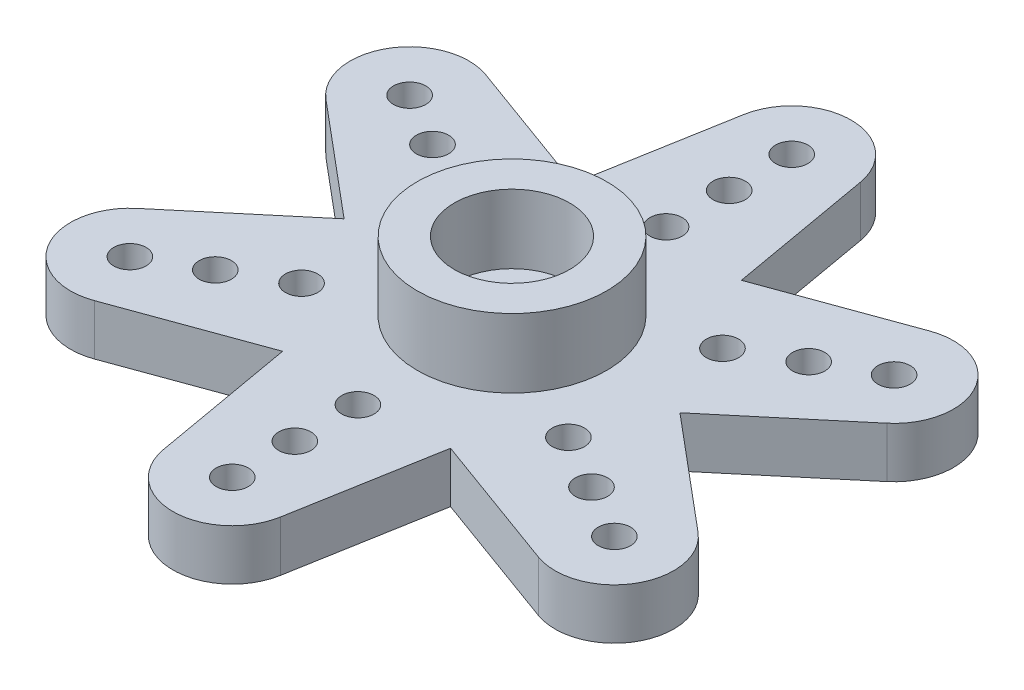
SolidWorks part; units mm, degrees
ref_plane "Front Plane" through (0, 0, 0) normal (0, 0, 1) x (1, 0, 0)
ref_plane "Top Plane" through (0, 0, 0) normal (0, 1, 0) x (1, 0, 0)
ref_plane "Right Plane" through (0, 0, 0) normal (1, 0, 0) x (0, 0, -1)
sketch "Sketch1" plane through (0, 0, 0) normal (0, 1, 0) x (1, 0, 0)
  circle A0 centre (0, 0) radius 15.75
  dimension "D1" = 31.5
extrude "Boss-Extrude1" add sketch "Sketch1" along normal blind 2.35
sketch "Sketch2" plane through (0, 2.35, 0) normal (0, 1, 0) x (1, 0, 0)
  line L0 (0, 0) -> (0, 50000) construction
  line L1 (0, 0) -> (-43301.2702, 25000) construction
  line L2 (0, 0) -> (-25000, 43301.2702) construction
  line L3 (-3.9, 6.755) -> (8678.5089, 49247.1426) construction
  line L4 (-3.9, 6.755) -> (-46988.531, 17107.7622) construction
  line L5 (-3.9, 6.755) -> (-2.7157, 13.4712)
  line L6 (0, 15.75) -> (0, 13.7424)
  line L7 (0, 12.2424) -> (0, 10.8376)
  line L8 (0, 9.3376) -> (0, 7.9061)
  line L11 (-3.9, 6.755) -> (-46988.531, 17107.7622) construction
  line L12 (0, 0) -> (-43301.2702, 25000) construction
  line L13 (-5.5478, 3.203) -> (0, 0)
  line L14 (-8.0866, 4.6688) -> (-6.8469, 3.953)
  line L15 (-10.6022, 6.1212) -> (-9.3856, 5.4188)
  line L16 (-13.6399, 7.875) -> (-11.9012, 6.8712)
  line L17 (-3.9, 6.755) -> (-10.3085, 9.0875)
  line L18 (3.9, 6.755) -> (10.3085, 9.0875)
  line L19 (3.9, 6.755) -> (2.7157, 13.4712)
  line L20 (0, 15.75) -> (0, 13.7424)
  line L21 (0, 12.2424) -> (0, 10.8376)
  line L22 (0, 9.3376) -> (0, 7.9061)
  line L23 (0, 6.4061) -> (0, 0)
  line L24 (5.5478, 3.203) -> (0, 0)
  line L25 (8.0866, 4.6688) -> (6.8469, 3.953)
  line L26 (10.6022, 6.1212) -> (9.3856, 5.4188)
  line L27 (13.6399, 7.875) -> (11.9012, 6.8712)
  line L28 (7.8, 0) -> (13.0243, -4.3837)
  line L29 (7.8, 0) -> (13.0243, 4.3837)
  line L30 (13.6399, 7.875) -> (11.9012, 6.8712)
  line L31 (10.6022, 6.1212) -> (9.3856, 5.4188)
  line L32 (8.0866, 4.6688) -> (6.8469, 3.953)
  line L33 (5.5478, 3.203) -> (0, 0)
  line L34 (5.5478, -3.203) -> (0, 0)
  line L35 (8.0866, -4.6688) -> (6.8469, -3.953)
  line L36 (10.6022, -6.1212) -> (9.3856, -5.4188)
  line L37 (13.6399, -7.875) -> (11.9012, -6.8712)
  line L38 (3.9, -6.755) -> (2.7157, -13.4712)
  line L39 (3.9, -6.755) -> (10.3085, -9.0875)
  line L40 (13.6399, -7.875) -> (11.9012, -6.8712)
  line L41 (10.6022, -6.1212) -> (9.3856, -5.4188)
  line L42 (8.0866, -4.6688) -> (6.8469, -3.953)
  line L43 (5.5478, -3.203) -> (0, 0)
  line L44 (0, -6.4061) -> (0, 0)
  line L45 (0, -9.3376) -> (0, -7.9061)
  line L46 (0, -12.2424) -> (0, -10.8376)
  line L47 (0, -15.75) -> (0, -13.7424)
  line L48 (-3.9, -6.755) -> (-10.3085, -9.0875)
  line L49 (-3.9, -6.755) -> (-2.7157, -13.4712)
  line L50 (0, -15.75) -> (0, -13.7424)
  line L51 (0, -12.2424) -> (0, -10.8376)
  line L52 (0, -9.3376) -> (0, -7.9061)
  line L53 (0, -6.4061) -> (0, 0)
  line L54 (-5.5478, -3.203) -> (0, 0)
  line L55 (-8.0866, -4.6688) -> (-6.8469, -3.953)
  line L56 (-10.6022, -6.1212) -> (-9.3856, -5.4188)
  line L57 (-13.6399, -7.875) -> (-11.9012, -6.8712)
  line L58 (-7.8, 0) -> (-13.0243, 4.3837)
  line L59 (-7.8, 0) -> (-13.0243, -4.3837)
  line L60 (-13.6399, -7.875) -> (-11.9012, -6.8712)
  line L61 (-10.6022, -6.1212) -> (-9.3856, -5.4188)
  line L62 (-8.0866, -4.6688) -> (-6.8469, -3.953)
  line L63 (-5.5478, -3.203) -> (0, 0)
  line L64 (-5.5478, 3.203) -> (0, 0)
  line L65 (-8.0866, 4.6688) -> (-6.8469, 3.953)
  line L66 (-10.6022, 6.1212) -> (-9.3856, 5.4188)
  line L67 (-13.6399, 7.875) -> (-11.9012, 6.8712)
  arc A0 (0, 15.75) -> (-2.7157, 13.4712) centre (0, 12.9924) ccw
  circle A1 centre (0, 0) radius 15.75 construction
  arc A2 (0, 13.7424) -> (0, 12.2424) centre (0, 12.9924) ccw
  arc A3 (0, 10.8376) -> (0, 9.3376) centre (0, 10.0876) ccw
  arc A4 (0, 7.9061) -> (0, 6.4061) centre (0, 7.1561) ccw
  arc A5 (-6.8469, 3.953) -> (-5.5478, 3.203) centre (-6.1974, 3.578) cw
  arc A6 (-9.3856, 5.4188) -> (-8.0866, 4.6688) centre (-8.7361, 5.0438) cw
  arc A7 (-11.9012, 6.8712) -> (-10.6022, 6.1212) centre (-11.2517, 6.4962) cw
  arc A8 (-13.6399, 7.875) -> (-10.3085, 9.0875) centre (-11.2517, 6.4962) cw
  arc A9 (0, 15.75) -> (2.7157, 13.4712) centre (0, 12.9924) cw
  arc A10 (0, 13.7424) -> (0, 12.2424) centre (0, 12.9924) cw
  arc A11 (0, 10.8376) -> (0, 9.3376) centre (0, 10.0876) cw
  arc A12 (0, 7.9061) -> (0, 6.4061) centre (0, 7.1561) cw
  arc A13 (6.8469, 3.953) -> (5.5478, 3.203) centre (6.1974, 3.578) ccw
  arc A14 (9.3856, 5.4188) -> (8.0866, 4.6688) centre (8.7361, 5.0438) ccw
  arc A15 (11.9012, 6.8712) -> (10.6022, 6.1212) centre (11.2517, 6.4962) ccw
  arc A16 (13.6399, 7.875) -> (10.3085, 9.0875) centre (11.2517, 6.4962) ccw
  arc A17 (13.6399, 7.875) -> (13.0243, 4.3837) centre (11.2517, 6.4962) cw
  arc A18 (11.9012, 6.8712) -> (10.6022, 6.1212) centre (11.2517, 6.4962) cw
  arc A19 (9.3856, 5.4188) -> (8.0866, 4.6688) centre (8.7361, 5.0438) cw
  arc A20 (6.8469, 3.953) -> (5.5478, 3.203) centre (6.1974, 3.578) cw
  arc A21 (6.8469, -3.953) -> (5.5478, -3.203) centre (6.1974, -3.578) ccw
  arc A22 (9.3856, -5.4188) -> (8.0866, -4.6688) centre (8.7361, -5.0438) ccw
  arc A23 (11.9012, -6.8712) -> (10.6022, -6.1212) centre (11.2517, -6.4962) ccw
  arc A24 (13.6399, -7.875) -> (13.0243, -4.3837) centre (11.2517, -6.4962) ccw
  arc A25 (13.6399, -7.875) -> (10.3085, -9.0875) centre (11.2517, -6.4962) cw
  arc A26 (11.9012, -6.8712) -> (10.6022, -6.1212) centre (11.2517, -6.4962) cw
  arc A27 (9.3856, -5.4188) -> (8.0866, -4.6688) centre (8.7361, -5.0438) cw
  arc A28 (6.8469, -3.953) -> (5.5478, -3.203) centre (6.1974, -3.578) cw
  arc A29 (0, -7.9061) -> (0, -6.4061) centre (0, -7.1561) ccw
  arc A30 (0, -10.8376) -> (0, -9.3376) centre (0, -10.0876) ccw
  arc A31 (0, -13.7424) -> (0, -12.2424) centre (0, -12.9924) ccw
  arc A32 (0, -15.75) -> (2.7157, -13.4712) centre (0, -12.9924) ccw
  arc A33 (0, -15.75) -> (-2.7157, -13.4712) centre (0, -12.9924) cw
  arc A34 (0, -13.7424) -> (0, -12.2424) centre (0, -12.9924) cw
  arc A35 (0, -10.8376) -> (0, -9.3376) centre (0, -10.0876) cw
  arc A36 (0, -7.9061) -> (0, -6.4061) centre (0, -7.1561) cw
  arc A37 (-6.8469, -3.953) -> (-5.5478, -3.203) centre (-6.1974, -3.578) ccw
  arc A38 (-9.3856, -5.4188) -> (-8.0866, -4.6688) centre (-8.7361, -5.0438) ccw
  arc A39 (-11.9012, -6.8712) -> (-10.6022, -6.1212) centre (-11.2517, -6.4962) ccw
  arc A40 (-13.6399, -7.875) -> (-10.3085, -9.0875) centre (-11.2517, -6.4962) ccw
  arc A41 (-13.6399, -7.875) -> (-13.0243, -4.3837) centre (-11.2517, -6.4962) cw
  arc A42 (-11.9012, -6.8712) -> (-10.6022, -6.1212) centre (-11.2517, -6.4962) cw
  arc A43 (-9.3856, -5.4188) -> (-8.0866, -4.6688) centre (-8.7361, -5.0438) cw
  arc A44 (-6.8469, -3.953) -> (-5.5478, -3.203) centre (-6.1974, -3.578) cw
  arc A45 (-6.8469, 3.953) -> (-5.5478, 3.203) centre (-6.1974, 3.578) ccw
  arc A46 (-9.3856, 5.4188) -> (-8.0866, 4.6688) centre (-8.7361, 5.0438) ccw
  arc A47 (-11.9012, 6.8712) -> (-10.6022, 6.1212) centre (-11.2517, 6.4962) ccw
  arc A48 (-13.6399, 7.875) -> (-13.0243, 4.3837) centre (-11.2517, 6.4962) ccw
  point P9 (-3.9, 6.755)
  point P161 (0, 0)
  circle M16 centre (0, 0) radius 15.75
  dimension "D6" = 1.5
  dimension "D1" = 60
  dimension "D2" = 30
  dimension "D3" = 40
  dimension "D4" = 40
  dimension "D5" = 7.8
extrude "Cut-Extrude2" cut sketch "Sketch2" against normal blind 2.35 contours A42 A39 | A43 A38 | A44 A37 | A7 A47 | A6 A46 | A5 A45 | A10 A2 | A12 A4 | A11 A3 | A20 A13 | A19 A14 | A18 A15 | A28 A21 | A27 A22 | A26 A23 | A36 A29 | A35 A30 | A34 A31 | A40 A33 L49 L48 M16 | A48 A41 L59 L58 M16 | A8 L17 L5 A0 M16 | A16 A9 L19 L18 M16 | A24 A17 L29 L28 M16 | A32 A25 L39 L38 M16
sketch "Sketch3" plane through (0, 2.35, 0) normal (0, 1, 0) x (1, 0, 0)
  circle A0 centre (0, 0) radius 4.4
  circle A1 centre (0, 0) radius 2.68
  dimension "D1" = 1.72
extrude "Boss-Extrude2" add sketch "Sketch3" along normal blind 3.2
sketch "Sketch4" plane through (0, 2.35, 0) normal (0, 1, 0) x (1, 0, 0)
  circle A0 centre (0, 0) radius 1.5
extrude "Cut-Extrude3" cut sketch "Sketch4" against normal through all
